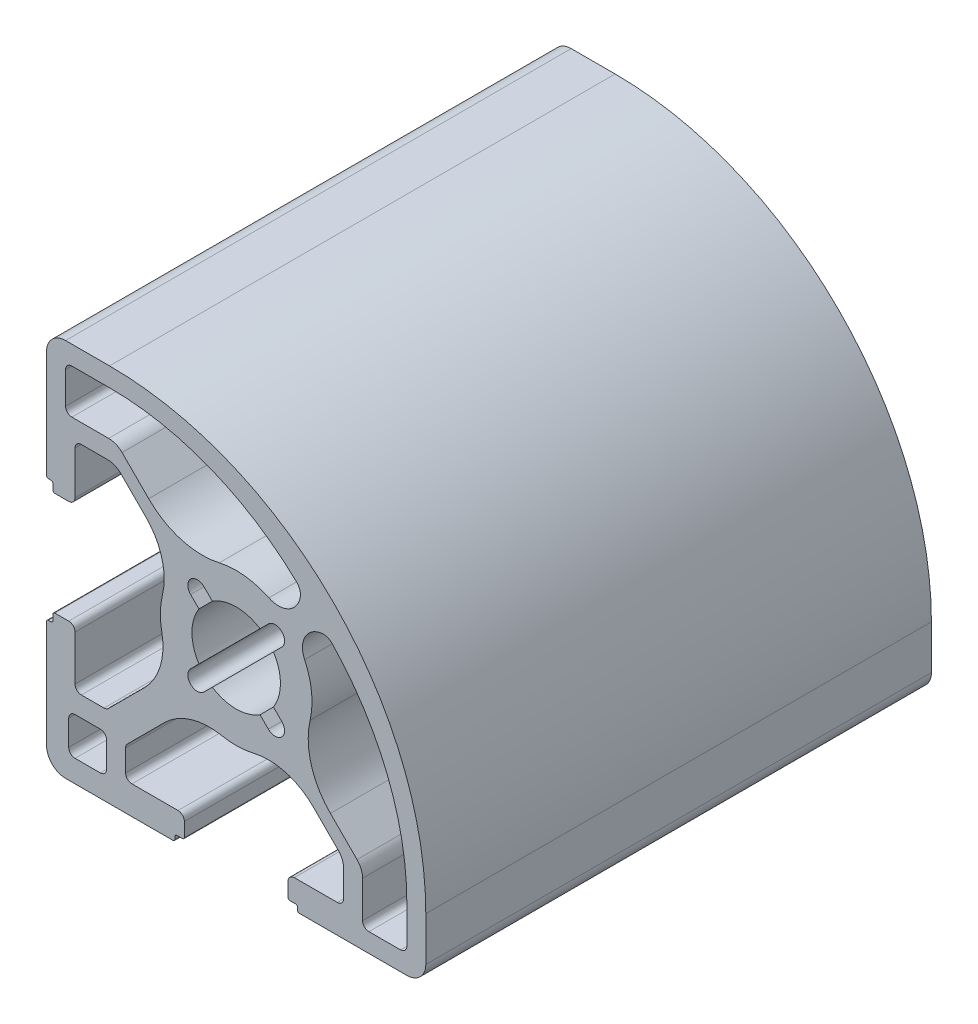
SolidWorks part; units mm, degrees
material "6061 Alaşım"
ref_plane "Ön Düzlem" through (0, 0, 0) normal (0, 0, 1) x (1, 0, 0)
ref_plane "Üst Düzlem" through (0, 0, 0) normal (0, 1, 0) x (1, 0, 0)
ref_plane "Sağ Düzlem" through (0, 0, 0) normal (1, 0, 0) x (0, 0, -1)
sketch "Çizim1" plane through (0, 0, 0) normal (0, 0, 1) x (1, 0, 0)
  line L0 (-15, 0) -> (15, 0) construction
  line L1 (-15, -15) -> (15, -15) construction
  line L2 (-15, -15) -> (-15, 15) construction
  line L3 (-15, 15) -> (15, 15) construction
  line L4 (15, -15) -> (15, 15) construction
  line L5 (-15, -15) -> (15, 15) construction
  line L6 (-15, 15) -> (15, -15) construction
  line L7 (-13.25, -4.1) -> (-14.35, -4.1)
  line L8 (-14.5, -4.25) -> (-14.5, -4.7)
  line L9 (-14.65, -4.85) -> (-14.85, -4.85)
  line L10 (-15, -5) -> (-15, -13.5)
  line L11 (-13.5, -15) -> (-5, -15)
  line L12 (-4.85, -14.85) -> (-4.85, -14.65)
  line L13 (-4.7, -14.5) -> (-4.25, -14.5)
  line L14 (-4.1, -14.35) -> (-4.1, -13.25)
  line L15 (-4.6, -12.75) -> (-8.25, -12.75)
  line L16 (-8.75, -12.25) -> (-8.75, -10.5481)
  line L17 (-8.6036, -10.1945) -> (-5.6653, -7.2563)
  line L18 (-12.75, -4.6) -> (-12.75, -8.159)
  line L19 (-12.25, -8.659) -> (-10.4571, -8.659)
  line L20 (-10.1036, -8.5126) -> (-7.2563, -5.6653)
  line L21 (-13.25, -10.75) -> (-13.25, -12.75)
  line L22 (-12.75, -13.25) -> (-10.75, -13.25)
  line L23 (-10.25, -12.75) -> (-10.25, -10.75)
  line L24 (-10.75, -10.25) -> (-12.75, -10.25)
  line L25 (0, 0) -> (0, -15) construction
  line L26 (-14.85, 4.85) -> (-14.65, 4.85)
  line L27 (-14.5, 4.7) -> (-14.5, 4.25)
  line L28 (-14.35, 4.1) -> (-13.25, 4.1)
  line L29 (-12.75, 4.6) -> (-12.75, 8)
  line L30 (-12.25, 8.5) -> (-10.182, 8.5)
  line L31 (-9.1213, 8.0607) -> (-7.1612, 6.1006)
  line L32 (-15, 5) -> (-15, 13.5)
  line L33 (-13.5, 15) -> (-10.0204, 15)
  line L34 (-13, 13.5) -> (-10.0204, 13.5)
  line L35 (7.2218, 7.2218) -> (4.2426, 4.2426)
  line L36 (4.2426, 4.2426) -> (2.4749, 2.4749)
  line L37 (-13.5, 10.5) -> (-13.5, 13)
  line L38 (-13, 10) -> (-10.091, 10)
  line L39 (-9.0303, 9.5607) -> (-6.9237, 7.454)
  line L40 (15, -15) -> (15, 15) construction
  line L41 (15, -13.5) -> (15, -10.0204)
  line L42 (5, -15) -> (13.5, -15)
  line L43 (4.7, -14.5) -> (4.25, -14.5)
  line L44 (4.1, -14.35) -> (4.1, -13.25)
  line L45 (4.6, -12.75) -> (8, -12.75)
  line L46 (8.5, -12.25) -> (8.5, -10.182)
  line L47 (8.0607, -9.1213) -> (6.1006, -7.1612)
  line L48 (9.5607, -9.0303) -> (7.454, -6.9237)
  line L49 (10, -13) -> (10, -10.091)
  line L50 (10.5, -13.5) -> (13, -13.5)
  line L51 (13.5, -13) -> (13.5, -10.0204)
  line L52 (-3.6062, 2.5456) -> (-2.9477, 1.8871)
  line L53 (-2.5456, 3.6062) -> (-1.8871, 2.9477)
  line L54 (3.6062, 2.5456) -> (2.9477, 1.8871)
  line L55 (2.5456, 3.6062) -> (1.8871, 2.9477)
  line L56 (2.5456, -3.6062) -> (1.8871, -2.9477)
  line L57 (3.6062, -2.5456) -> (2.9477, -1.8871)
  line L58 (-3.6062, -2.5456) -> (-2.9477, -1.8871)
  line L59 (-2.5456, -3.6062) -> (-1.8871, -2.9477)
  line L60 (4.85, -14.65) -> (4.85, -14.85)
  circle A0 centre (0, 0) radius 3.5 construction
  arc A1 (-10.0204, 15) -> (7.2218, 7.2218) centre (-10.0204, -8) cw construction
  circle A2 centre (0, 0) radius 6
  arc A3 (-6.9237, 7.454) -> (-1.3405, 5.8483) centre (-2.6811, 11.6967) ccw
  arc A4 (-10.0204, 13.5) -> (4.7715, 7.6029) centre (-10.0204, -8) cw
  arc A5 (2.5876, 5.4133) -> (5.0716, 6.7237) centre (3.3424, 6.9922) ccw
  arc A6 (4.7715, 7.6029) -> (5.0716, 6.7237) centre (4.0835, 6.8771) cw
  arc A7 (-1.3405, 5.8483) -> (2.5876, 5.4133) centre (0, 0) cw
  arc A8 (-5.8346, 1.3991) -> (-5.8865, -1.1617) centre (0, 0) ccw
  arc A9 (-7.2563, -5.6653) -> (-5.8865, -1.1617) centre (-10.7918, -2.1298) ccw
  arc A10 (-7.1612, 6.1006) -> (-5.8346, 1.3991) centre (-10.6968, 2.565) cw
  arc A11 (0, -6) -> (-1.1617, -5.8865) centre (0, 0) cw
  arc A12 (-5.6653, -7.2563) -> (-1.1617, -5.8865) centre (-2.1298, -10.7918) cw
  arc A13 (-5.853, 1.3199) -> (-1.3405, 5.8483) centre (0, 0) cw construction
  arc A14 (2.5876, 5.4133) -> (4.2426, 4.2426) centre (0, 0) cw
  arc A15 (-10.182, 8.5) -> (-9.1213, 8.0607) centre (-10.182, 7) cw
  arc A16 (-10.091, 10) -> (-9.0303, 9.5607) centre (-10.091, 8.5) cw
  arc A17 (-15, 13.5) -> (-13.5, 15) centre (-13.5, 13.5) cw
  arc A18 (-4.1, -13.25) -> (-4.6, -12.75) centre (-4.6, -13.25) ccw
  arc A19 (-8.75, -10.5481) -> (-8.6036, -10.1945) centre (-8.25, -10.5481) cw
  arc A20 (-8.25, -12.75) -> (-8.75, -12.25) centre (-8.25, -12.25) cw
  arc A21 (-13.25, -12.75) -> (-12.75, -13.25) centre (-12.75, -12.75) ccw
  arc A22 (-10.75, -13.25) -> (-10.25, -12.75) centre (-10.75, -12.75) ccw
  arc A23 (-10.25, -10.75) -> (-10.75, -10.25) centre (-10.75, -10.75) ccw
  arc A24 (-13.25, -10.75) -> (-12.75, -10.25) centre (-12.75, -10.75) cw
  arc A25 (-10.4571, -8.659) -> (-10.1036, -8.5126) centre (-10.4571, -8.159) ccw
  arc A26 (-12.75, -8.159) -> (-12.25, -8.659) centre (-12.25, -8.159) ccw
  arc A27 (-13.25, -4.1) -> (-12.75, -4.6) centre (-13.25, -4.6) cw
  arc A28 (-13.25, 4.1) -> (-12.75, 4.6) centre (-13.25, 4.6) ccw
  arc A29 (-13, 13.5) -> (-13.5, 13) centre (-13, 13) ccw
  arc A30 (-13.5, 10.5) -> (-13, 10) centre (-13, 10.5) ccw
  arc A31 (-12.75, 8) -> (-12.25, 8.5) centre (-12.25, 8) cw
  arc A32 (-4.25, -14.5) -> (-4.1, -14.35) centre (-4.25, -14.35) ccw
  arc A33 (-4.85, -14.65) -> (-4.7, -14.5) centre (-4.7, -14.65) cw
  arc A34 (-5, -15) -> (-4.85, -14.85) centre (-5, -14.85) ccw
  arc A35 (-14.5, 4.25) -> (-14.35, 4.1) centre (-14.35, 4.25) ccw
  arc A36 (-14.65, 4.85) -> (-14.5, 4.7) centre (-14.65, 4.7) cw
  arc A37 (-14.85, 4.85) -> (-15, 5) centre (-14.85, 5) cw
  arc A38 (-14.35, -4.1) -> (-14.5, -4.25) centre (-14.35, -4.25) ccw
  arc A39 (-14.5, -4.7) -> (-14.65, -4.85) centre (-14.65, -4.7) cw
  arc A40 (-14.85, -4.85) -> (-15, -5) centre (-14.85, -5) ccw
  arc A41 (-15, -13.5) -> (-13.5, -15) centre (-13.5, -13.5) ccw
  arc A42 (7.2218, 7.2218) -> (15, -10.0204) centre (-8, -10.0204) cw construction
  arc A43 (13.5, -15) -> (15, -13.5) centre (13.5, -13.5) ccw
  arc A44 (4.85, -14.85) -> (5, -15) centre (5, -14.85) ccw
  arc A45 (4.85, -14.65) -> (4.7, -14.5) centre (4.7, -14.65) ccw
  arc A46 (4.25, -14.5) -> (4.1, -14.35) centre (4.25, -14.35) cw
  arc A47 (4.1, -13.25) -> (4.6, -12.75) centre (4.6, -13.25) cw
  arc A48 (8, -12.75) -> (8.5, -12.25) centre (8, -12.25) ccw
  arc A49 (6.1006, -7.1612) -> (1.3991, -5.8346) centre (2.565, -10.6968) ccw
  arc A50 (7.454, -6.9237) -> (5.8483, -1.3405) centre (11.6967, -2.6811) cw
  arc A51 (10, -10.091) -> (9.5607, -9.0303) centre (8.5, -10.091) ccw
  arc A52 (10.5, -13.5) -> (10, -13) centre (10.5, -13) cw
  arc A53 (13.5, -13) -> (13, -13.5) centre (13, -13) cw
  arc A54 (13.5, -10.0204) -> (7.6029, 4.7715) centre (-8, -10.0204) ccw
  arc A55 (7.6029, 4.7715) -> (6.7237, 5.0716) centre (6.8771, 4.0835) ccw
  arc A56 (5.4133, 2.5876) -> (6.7237, 5.0716) centre (6.9922, 3.3424) cw
  arc A57 (5.8483, -1.3405) -> (5.4133, 2.5876) centre (0, 0) ccw
  arc A58 (8.5, -10.182) -> (8.0607, -9.1213) centre (7, -10.182) ccw
  arc A59 (-1.1617, -5.8865) -> (1.3991, -5.8346) centre (0, 0) ccw
  arc A60 (-3.6062, 2.5456) -> (-2.5456, 3.6062) centre (-3.0759, 3.0759) cw
  arc A61 (2.5456, 3.6062) -> (3.6062, 2.5456) centre (3.0759, 3.0759) cw
  arc A62 (3.6062, -2.5456) -> (2.5456, -3.6062) centre (3.0759, -3.0759) cw
  arc A63 (-2.5456, -3.6062) -> (-3.6062, -2.5456) centre (-3.0759, -3.0759) cw
  arc A64 (-1.8871, 2.9477) -> (1.8871, 2.9477) centre (0, 0) cw
  arc A65 (2.9477, 1.8871) -> (2.9477, -1.8871) centre (0, 0) cw
  arc A66 (1.8871, -2.9477) -> (-1.8871, -2.9477) centre (0, 0) cw
  arc A67 (-2.9477, -1.8871) -> (-2.9477, 1.8871) centre (0, 0) cw
  arc A68 (-5.8865, -1.1617) -> (-1.1617, -5.8865) centre (0, 0) ccw
  arc A69 (1.3991, -5.8346) -> (5.8483, -1.3405) centre (0, 0) ccw
  arc A70 (-10.0204, 15) -> (15, -10.0204) centre (-10.0204, -10.0204) cw
  point P0 (0, 0)
  point P30 (-4.1, -13.8)
  point P56 (5.0607, 7.3235)
  point P58 (-4.9629, -3.3719)
  point P61 (-4.7397, 3.679)
  point P66 (-3.3719, -4.9629)
  point P87 (-13.25, -13.25)
  point P90 (-10.25, -13.25)
  point P93 (-10.25, -10.25)
  point P98 (-10.25, -8.659)
  point P107 (-13.5, 13.5)
  point P110 (-13.5, 10)
  point P115 (-4.1, -14.5)
  point P118 (-4.85, -14.5)
  point P121 (-4.85, -15)
  point P124 (-14.5, 4.1)
  point P127 (-14.5, 4.85)
  point P130 (-15, 4.85)
  point P133 (-14.5, -4.1)
  point P136 (-14.5, -4.85)
  point P139 (-15, -4.85)
  point P151 (4.85, -15)
  point P212 (0, 0)
  dimension "D17" = 7
  dimension "D23" = 23
  dimension "D24" = 1.75
  dimension "D27" = 12
  dimension "D28" = 11
  dimension "D29" = 6
  dimension "D31" = 1
  dimension "D32" = 5
  dimension "D33" = 5
  dimension "D34" = 1.5
  dimension "D35" = 0.5
  dimension "D36" = 0.15
  dimension "D37" = 1.5
  dimension "D38" = 0.75
  dimension "D1" = 30
  dimension "D2" = 30
  dimension "D3" = 4.1
  dimension "D4" = 3
  dimension "D5" = 3
  dimension "D6" = 2.25
  dimension "D7" = 2.25
  dimension "D8" = 0.75
  dimension "D9" = 0.5
  dimension "D10" = 0.5
  dimension "D11" = 0.75
  dimension "D12" = 4.1
  dimension "D13" = 1.125
  dimension "D14" = 2.25
  dimension "D15" = 1.5
  dimension "D16" = 1.75
  dimension "D18" = 4.1
  dimension "D19" = 0.75
  dimension "D20" = 1.5
  dimension "D21" = 8.5
  dimension "D22" = 3.5
  dimension "D25" = 0.75
  dimension "D26" = 0.75
  dimension "D30" = 1.6
  dimension "D39" = 4.35
  dimension "D40" = 4
extrude "Yükseklik-Ekstrüzyon2" add sketch "Çizim1" against normal blind 40
